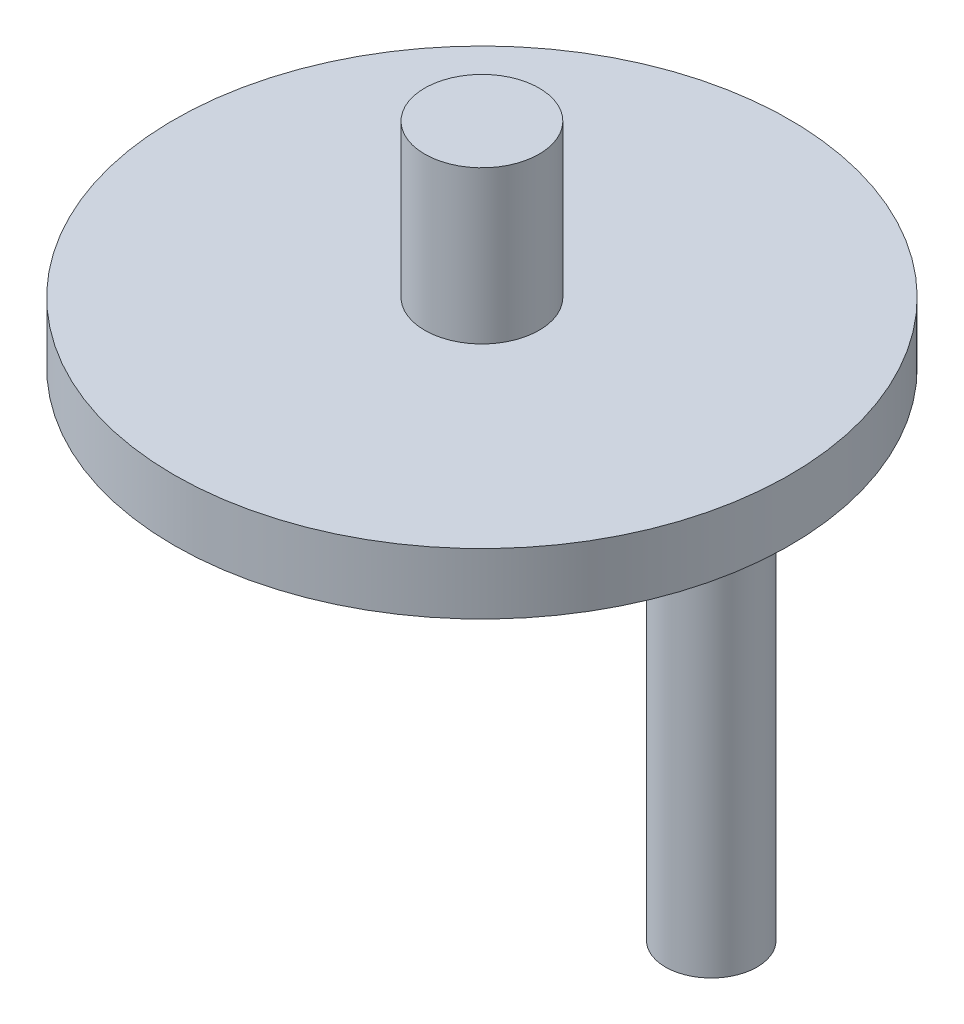
SolidWorks part; units mm, degrees
ref_plane "Front Plane" through (0, 0, 0) normal (0, 0, 1) x (1, 0, 0)
ref_plane "Top Plane" through (0, 0, 0) normal (0, 1, 0) x (1, 0, 0)
ref_plane "Right Plane" through (0, 0, 0) normal (1, 0, 0) x (0, 0, -1)
sketch "Sketch1" plane through (0, 0, 0) normal (0, 1, 0) x (1, 0, 0)
  circle A0 centre (0, 0) radius 40.34
extrude "Boss-Extrude1" add sketch "Sketch1" against normal blind 8
sketch "Sketch2" plane through (0, 0, 0) normal (0, 1, 0) x (1, 0, 0)
  circle A0 centre (0, 0) radius 7.5
extrude "Boss-Extrude2" add sketch "Sketch2" along normal blind 20
sketch "Sketch3" plane through (0, -8, 0) normal (0, -1, 0) x (1, 0, 0)
  arc A0 (11.1037, 16.6345) -> (11.1037, -16.6345) centre (0, 0) ccw
  arc A1 (11.1037, 16.6345) -> (11.1037, -16.6345) centre (30.06, 0) ccw
  dimension "D1" = 30.06
  dimension "D2" = 40
  dimension "D3" = 50.44
extrude "Boss-Extrude3" add sketch "Sketch3" along normal blind 10
sketch "Sketch4" plane through (0, -8, 0) normal (0, -1, 0) x (1, 0, 0)
  circle A0 centre (30.06, 0) radius 6
  point P2 (0, 0)
extrude "Boss-Extrude4" add sketch "Sketch4" along normal blind 50
